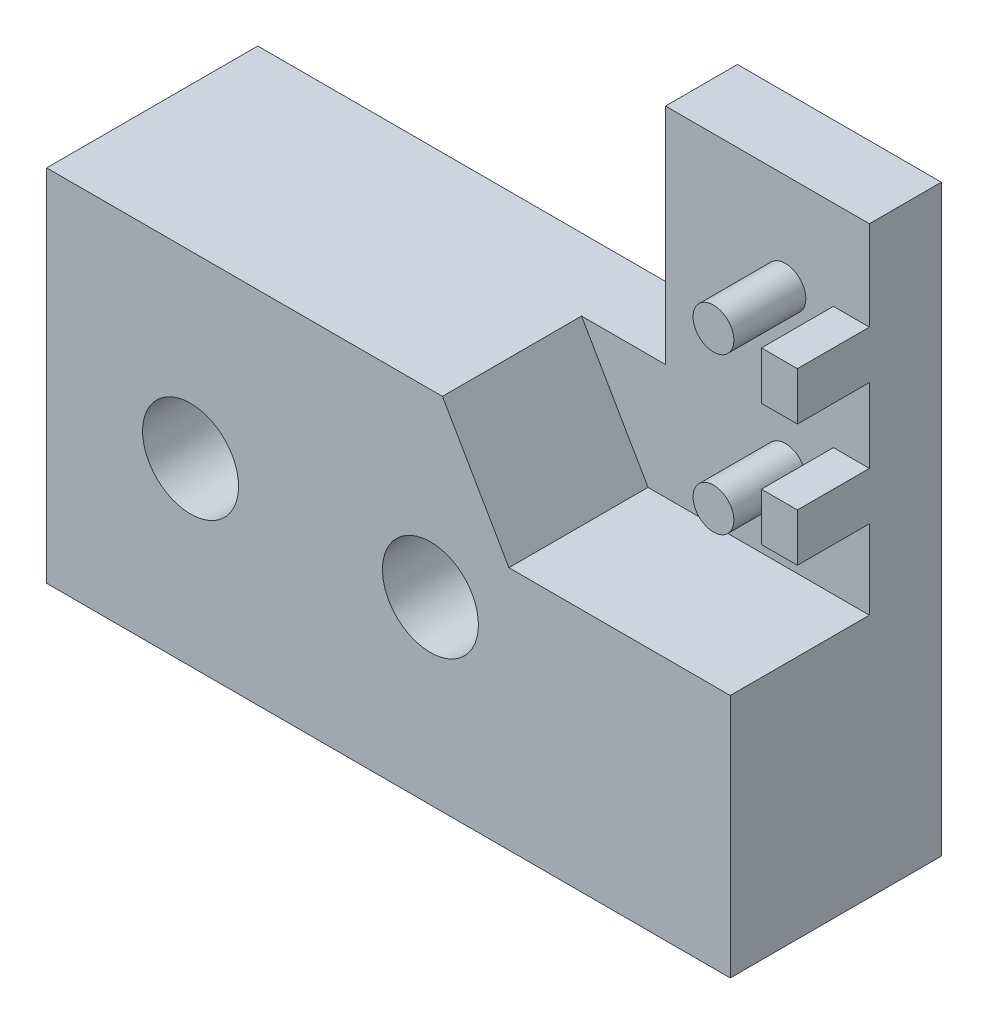
SolidWorks part; units mm, degrees
ref_plane "前视基准面" through (0, 0, 0) normal (0, 0, 1) x (1, 0, 0)
ref_plane "上视基准面" through (0, 0, 0) normal (0, 1, 0) x (1, 0, 0)
ref_plane "右视基准面" through (0, 0, 0) normal (1, 0, 0) x (0, 0, -1)
other "Configuration Table"
sketch "草图1" plane through (0, 0, 0) normal (0, 0, 1) x (1, 0, 0)
  line L0 (0, 0) -> (-28.5, 0)
  line L1 (-28.5, 0) -> (-28.5, 15)
  line L2 (-28.5, 15) -> (-8.5, 15)
  line L3 (-8.5, 15) -> (-8.5, 24.333)
  line L4 (-8.5, 24.333) -> (0, 24.333)
  line L5 (0, 24.333) -> (0, 0)
  dimension "D1" = 28.5
  dimension "D2" = 15
  dimension "D3" = 24.333
  dimension "D4" = 8.5
extrude "凸台-拉伸1" add sketch "草图1" along normal blind 3
sketch "草图2" plane through (0, 0, 3) normal (0, 0, 1) x (1, 0, 0)
  line L0 (-12, 15) -> (-9.2287, 10.2)
  line L1 (-8.5, 15) -> (-28.5, 15) construction
  line L2 (-9.2287, 10.2) -> (0, 10.2)
  line L3 (0, 0) -> (0, 24.333) construction
  line L4 (-8.5, 24.333) -> (-8.5, 15) construction
  line L5 (-12, 15) -> (-28.5, 15)
  line L6 (-28.5, 15) -> (-28.5, 0)
  line L7 (-28.5, 0) -> (0, 0)
  line L8 (0, 0) -> (0, 10.2)
  dimension "D1" = 120
  dimension "D2" = 4.8
  dimension "D3" = 3.5
extrude "凸台-拉伸2" add sketch "草图2" along normal blind 5.8
sketch "草图3" plane through (0, 0, 3) normal (0, 0, 1) x (1, 0, 0)
  line L0 (-3.5, 20.3) -> (-3.5, 13.8) construction
  line L1 (0, 10.2) -> (-9.2287, 10.2) construction
  line L2 (0, 13.5) -> (-1.5, 13.5)
  line L3 (0, 10.2) -> (0, 24.333) construction
  line L4 (-1.5, 13.5) -> (-1.5, 15.5)
  line L5 (-1.5, 15.5) -> (0, 15.5)
  line L6 (0, 10.2) -> (-9.2287, 10.2) construction
  line L7 (-3.5, 17.05) -> (0.6251, 17.05) construction
  line L8 (0, 15.6122) -> (0, 13.5)
  line L9 (0, 18.4878) -> (0, 20.6)
  line L10 (-1.5, 18.6) -> (0, 18.6)
  line L11 (-1.5, 20.6) -> (-1.5, 18.6)
  line L12 (0, 20.6) -> (-1.5, 20.6)
  circle A0 centre (-3.5, 13.8) radius 0.85
  circle A1 centre (-3.5, 20.3) radius 0.85
  line M9 (0, 10.2) -> (0, 24.333)
  dimension "D2" = 1.7
  dimension "D1" = 6.5
  dimension "D3" = 3.6
  dimension "D4" = 2
  dimension "D5" = 3.3
  dimension "D6" = 1.5
  dimension "D7" = 3.5
extrude "凸台-拉伸3" add sketch "草图3" along normal blind 3 contours L9 L12 L11 L10 | L5 L4 L2 M9 | A0 | A1
sketch "草图5" plane through (0, 0, 8.8) normal (0, 0, 1) x (1, 0, 0)
  line L0 (-28.5, 7.5) -> (0, 7.5)
  line L1 (-28.5, 15) -> (-28.5, 0) construction
  line L2 (0, 0) -> (0, 10.2) construction
  circle A0 centre (-22.5, 7.5) radius 2
  circle A1 centre (-12.5, 7.5) radius 2
  dimension "D1" = 4
  dimension "D2" = 4
  dimension "D3" = 10
  dimension "D4" = 6
extrude "切除-拉伸1" cut sketch "草图5" against normal up to surface (8.8 mm away) contours L0 A0 | L0 A0 | L0 A1 | L0 A1 up to face at (-12.3333, 13.111, 0)
